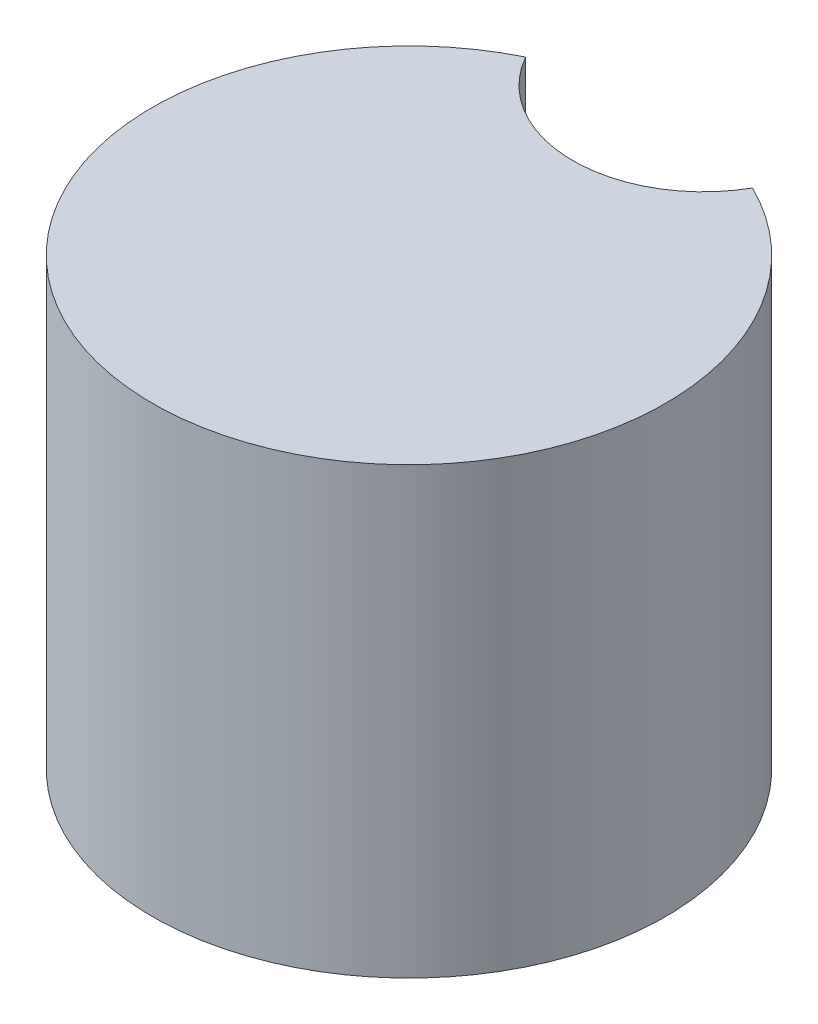
SolidWorks part; units mm, degrees
ref_plane "Front Plane" through (0, 0, 0) normal (0, 0, 1) x (1, 0, 0)
ref_plane "Top Plane" through (0, 0, 0) normal (0, 1, 0) x (1, 0, 0)
ref_plane "Right Plane" through (0, 0, 0) normal (1, 0, 0) x (0, 0, -1)
sketch "Sketch1" plane through (0, 0, 0) normal (0, 1, 0) x (1, 0, 0)
  circle A0 centre (0, 0) radius 75
  dimension "D1" = 150
extrude "Boss-Extrude1" add sketch "Sketch1" along normal blind 130
sketch "Sketch2" plane through (0, 130, 0) normal (0, 1, 0) x (1, 0, 0)
  line L0 (0, 86.0323) -> (0, 0) construction
  line L1 (0, 86.0323) -> (33.1606, 67.2709) construction
  circle A0 centre (0, 86.0323) radius 38.1
  circle A1 centre (0, 0) radius 75 construction
  dimension "D2" = 76.2
  dimension "D1" = 60.5
extrude "Cut-Extrude1" cut sketch "Sketch2" against normal through all
